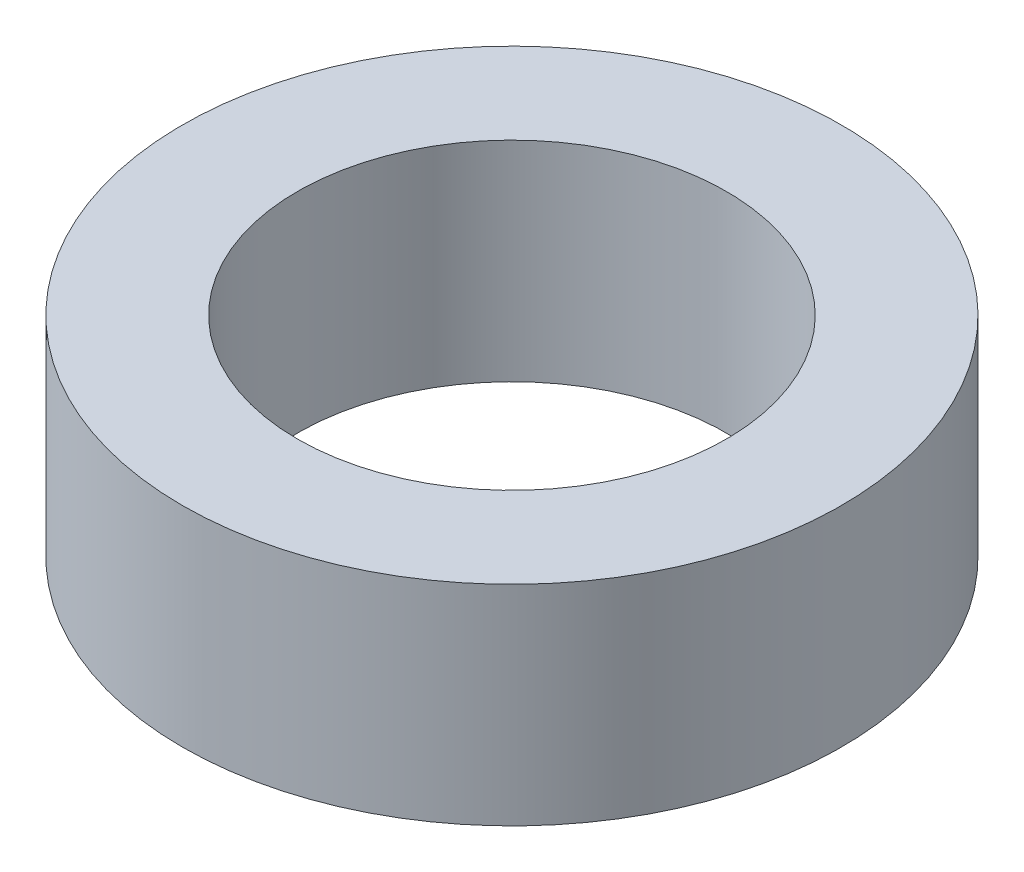
SolidWorks part; units mm, degrees
ref_plane "Front Plane" through (0, 0, 0) normal (0, 0, 1) x (1, 0, 0)
ref_plane "Top Plane" through (0, 0, 0) normal (0, 1, 0) x (1, 0, 0)
ref_plane "Right Plane" through (0, 0, 0) normal (1, 0, 0) x (0, 0, -1)
sketch "Sketch1" plane through (0, 0, 0) normal (0, 1, 0) x (1, 0, 0)
  circle A0 centre (0, 0) radius 3.15
  circle A1 centre (0, 0) radius 2.05
  dimension "D1" = 6.3
  dimension "D2" = 4.1
extrude "Boss-Extrude1" add sketch "Sketch1" along normal blind 2 contours A0 A1
